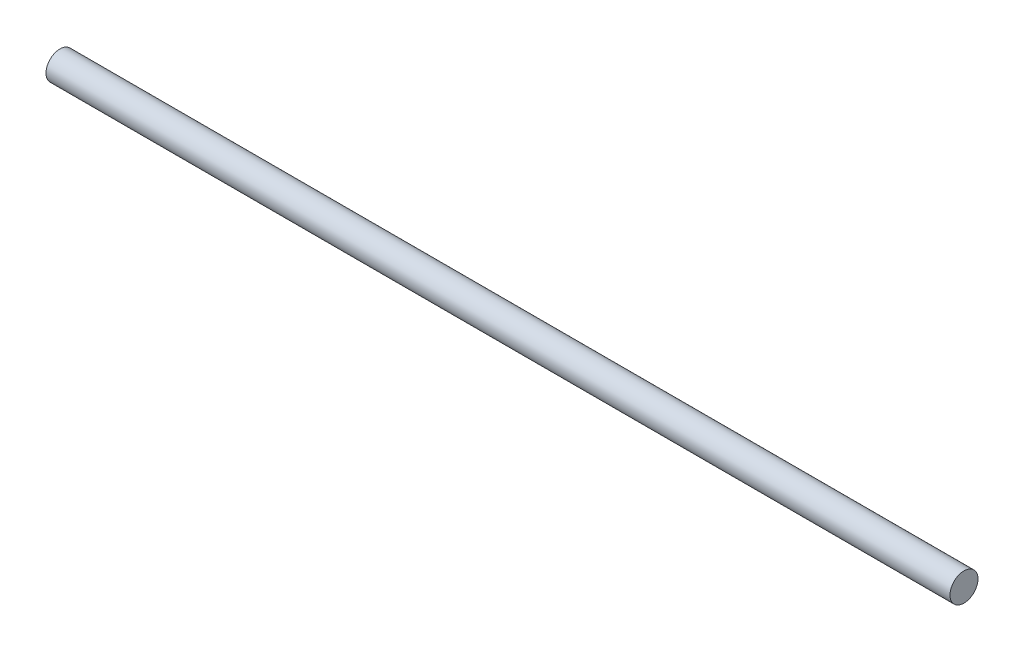
SolidWorks part; units mm, degrees
material "Zoltek Panex 33"
ref_plane "Front Plane" through (0, 0, 0) normal (0, 0, 1) x (1, 0, 0)
ref_plane "Top Plane" through (0, 0, 0) normal (0, 1, 0) x (1, 0, 0)
ref_plane "Right Plane" through (0, 0, 0) normal (1, 0, 0) x (0, 0, -1)
sketch "Sketch1" plane through (0, 0, 0) normal (1, 0, 0) x (0, 0, -1)
  circle A0 centre (0, 0) radius 9
  dimension "D1" = 18
extrude "Boss-Extrude1" add sketch "Sketch1" along normal mid plane 581
